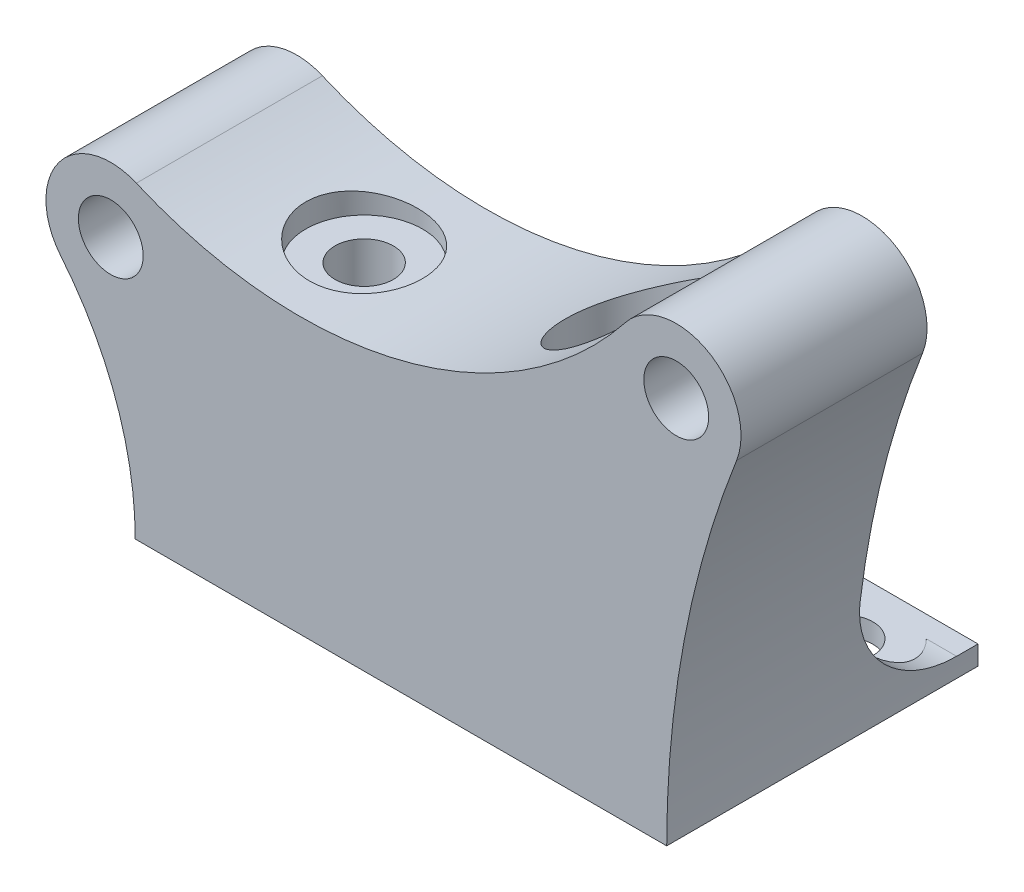
SolidWorks part; units mm, degrees
ref_plane "Płaszczyzna przednia" through (0, 0, 0) normal (0, 0, 1) x (1, 0, 0)
ref_plane "Płaszczyzna górna" through (0, 0, 0) normal (0, 1, 0) x (1, 0, 0)
ref_plane "Płaszczyzna prawa" through (0, 0, 0) normal (1, 0, 0) x (0, 0, -1)
sketch "Szkic1" plane through (0, 0, 0) normal (0, 0, 1) x (1, 0, 0)
  line L0 (-1.47, -60.54) -> (-83.47, -60.54)
  line L1 (-42.47, -60.54) -> (-42.47, -34.6311) construction
  circle A0 centre (-87.247, -22.09) radius 5
  circle A1 centre (0, 0) radius 5
  arc A2 (9.307, -3.6579) -> (-7.8435, 6.2031) centre (0, 0) ccw
  arc A3 (-83.3004, -12.9017) -> (-94.9714, -28.4408) centre (-87.247, -22.09) ccw
  arc A4 (-1.47, -60.54) -> (9.307, -3.6579) centre (154.0338, -60.54) cw
  arc A6 (-83.47, -60.54) -> (-94.9714, -28.4408) centre (-134.0133, -60.54) ccw
  arc A8 (-83.3004, -12.9017) -> (-7.8435, 6.2031) centre (-58.0422, 45.9032) ccw
  dimension "D1" = 10
  dimension "D2" = 10
  dimension "D7" = 20
  dimension "D8" = 20
  dimension "D9" = 155.5038
  dimension "D10" = 64
  dimension "D3" = 90
  dimension "D4" = 82
  dimension "D5" = 60.54
  dimension "D6" = 38.45
extrude "Dodanie-wyciągnięcie1" add sketch "Szkic1" along normal blind 28.7
sketch "Szkic3" plane through (0, 0, 0) normal (1, 0, 0) x (0, 0, -1)
  line L0 (0, -60.54) -> (0, -41.54)
  line L1 (0, -60.54) -> (19.3, -60.54)
  line L2 (-28.7, -60.54) -> (0, -60.54) construction
  line L7 (0, -27.09) -> (0, -17.09) construction
  line L8 (16, -57.54) -> (19.3, -57.54)
  line L9 (19.3, -57.54) -> (19.3, -60.54)
  line L10 (-28.7, -3.6579) -> (-28.7, -60.54) construction
  arc A0 (16, -57.54) -> (0, -41.54) centre (16, -41.54) cw
  dimension "D1" = 48
  dimension "D2" = 3
  dimension "D3" = 19
extrude "Dodanie-wyciągnięcie2" add sketch "Szkic3" against normal up to surface (87.1771 mm away)
sketch "Szkic4" plane through (0, 0, 0) normal (0, 0, 1) x (1, 0, 0)
  line L0 (-1.47, -60.54) -> (0, -60.54)
  line L1 (0, -60.54) -> (0, -41.54)
  line L2 (0, -41.54) -> (-0.3049, -41.54)
  arc A0 (-1.47, -60.54) -> (-0.3049, -41.54) centre (154.0338, -60.54) cw
  arc A1 (-0.3049, -41.54) -> (-1.47, -60.54) centre (154.0338, -60.54) ccw construction
extrude "Wytnij-wyciągnięcie1" cut sketch "Szkic4" against normal up to surface (19.3 mm away) up to face at (-41.7517, -59.0398, -19.3)
hole_wizard "Pogłębienie walcowe pod M8 Wkręt z łbem sześciokątnym z gniazdem1" positions "Szkic7" profile "Szkic9" counterbore size "M8" standard "ISO" end condition through all
sketch "Szkic7" plane through (0, 0, 0) normal (0, 1, 0) x (1, 0, 0)
  line L4 (-17.3275, -14.35) -> (-81.7271, -14.35) construction
  line L7 (-7.8435, 0) -> (-83.3004, 0) construction
  line L8 (-83.3004, -28.7) -> (-7.8435, -28.7) construction
  line L19 (-42.5001, -52.7037) -> (-42.5001, 17.1743) construction
  line L21 (-83.5591, 16) -> (-83.5591, 19.3) construction
  line L22 (-1.441, 19.3) -> (-1.441, 16) construction
  point P0 (-62.5001, -14.35)
  point P2 (-22.5001, -14.35)
  dimension "D1" = 40
sketch "Szkic9" plane through (-62.5001, 0, 14.35) normal (1, 0, 0) x (0, 0, 1)
  line L0 (0, 0) -> (0, 60.54)
  line L1 (0, 60.54) -> (4.5, 60.54)
  line L3 (4.5, 60.54) -> (4.5, 20.3)
  line L4 (4.5, 20.3) -> (9.0055, 20.3)
  line L5 (9.0055, 20.3) -> (9.0055, 0)
  line L7 (9.0055, 0) -> (0, 0)
  line L11 (0, -6.35) -> (0, 107.95) construction
  dimension "Średnica otworu na wylot" = 9
  dimension "Głębokość otworu na wylot" = 60.54
  dimension "Średnica pogłębienia walcowego" = 18.011
  dimension "Głębokość pogłębienia walcowego" = 20.3
hole_wizard "Pogłębienie walcowe pod M8 Wkręt z łbem sześciokątnym z gniazdem3" positions "Szkic10" profile "Szkic11" counterbore size "M8" standard "ISO" end condition through all
sketch "Szkic10" plane through (0, 0, 0) normal (0, 1, 0) x (1, 0, 0)
  line L0 (-25.0973, 9.65) -> (-137.2488, 9.65) construction
  line L3 (-83.5591, 19.3) -> (-1.441, 19.3) construction
  line L4 (-87.1771, 0) -> (-0.3049, 0) construction
  line L5 (-42.5001, -25.0215) -> (-42.5001, 41.234) construction
  line L7 (-1.441, 19.3) -> (-1.441, 16) construction
  line L8 (-83.5591, 16) -> (-83.5591, 19.3) construction
  point P0 (-72.5001, 9.65)
  point P2 (-12.5001, 9.65)
  dimension "D1" = 60
sketch "Szkic11" plane through (-72.5001, 0, -9.65) normal (1, 0, 0) x (0, 0, 1)
  line L0 (0, 0) -> (0, 60.54)
  line L1 (0, 60.54) -> (4.5, 60.54)
  line L3 (4.5, 60.54) -> (4.5, 57.54)
  line L4 (4.5, 57.54) -> (9.0055, 57.54)
  line L5 (9.0055, 57.54) -> (9.0055, 0)
  line L7 (9.0055, 0) -> (0, 0)
  line L11 (0, -6.35) -> (0, 107.95) construction
  dimension "Średnica otworu na wylot" = 9
  dimension "Głębokość otworu na wylot" = 60.54
  dimension "Średnica pogłębienia walcowego" = 18.011
  dimension "Głębokość pogłębienia walcowego" = 57.54
